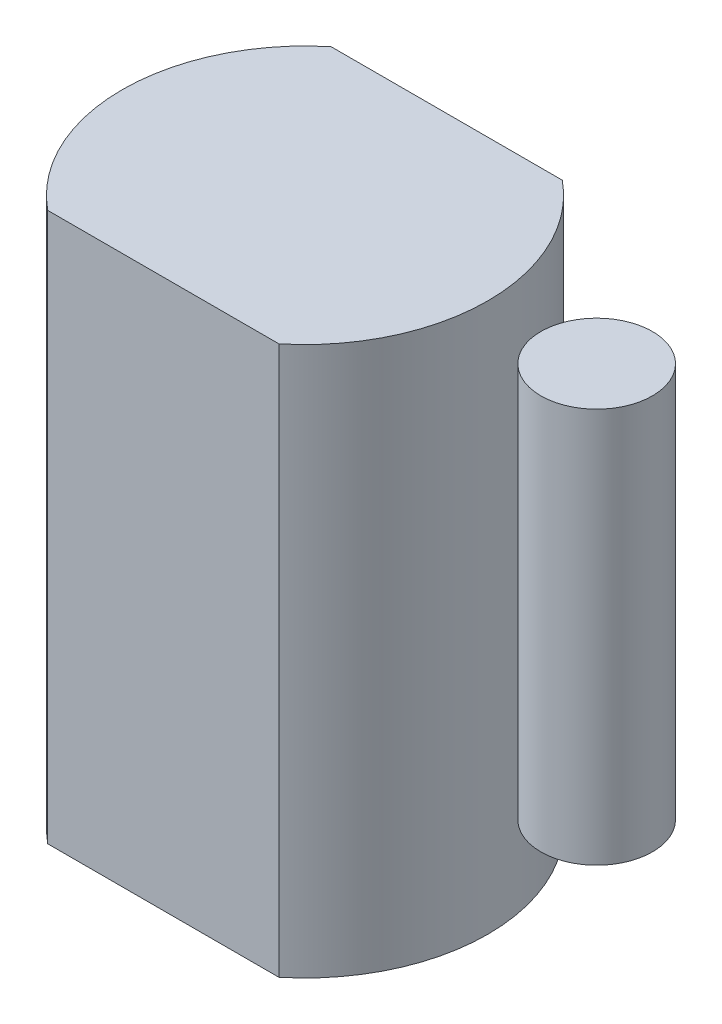
SolidWorks part; units mm, degrees
ref_plane "Plano frontal" through (0, 0, 0) normal (0, 0, 1) x (1, 0, 0)
ref_plane "Plano superior" through (0, 0, 0) normal (0, 1, 0) x (1, 0, 0)
ref_plane "Plano direito" through (0, 0, 0) normal (1, 0, 0) x (0, 0, -1)
sketch "Esboço2" plane through (0, 0, 0) normal (0, 1, 0) x (1, 0, 0)
  line L1 (-6.3196, -7.75) -> (6.3196, -7.75)
  line L3 (-6.3196, 7.75) -> (6.3196, 7.75)
  line L5 (-6.3196, -7.75) -> (6.3196, 7.75) construction
  line L6 (-6.3196, 7.75) -> (6.3196, -7.75) construction
  arc A0 (6.3196, 7.75) -> (6.3196, -7.75) centre (0, 0) cw
  arc A1 (-6.3196, 7.75) -> (-6.3196, -7.75) centre (0, 0) ccw
  point P0 (0, 0)
  dimension "D3" = 10
  dimension "D1" = 15.5
extrude "Ressalto-extrusão1" add sketch "Esboço2" along normal blind 30
sketch "Esboço3" plane through (0, 30, 0) normal (0, 1, 0) x (1, 0, 0)
  line L0 (0, 0) -> (15.95, 0) construction
  circle A0 centre (15.95, 0) radius 3.05
  dimension "D2" = 6.1
  dimension "D1" = 15.95
extrude "Ressalto-extrusão2" add sketch "Esboço3" against normal blind 21.6 separate body
